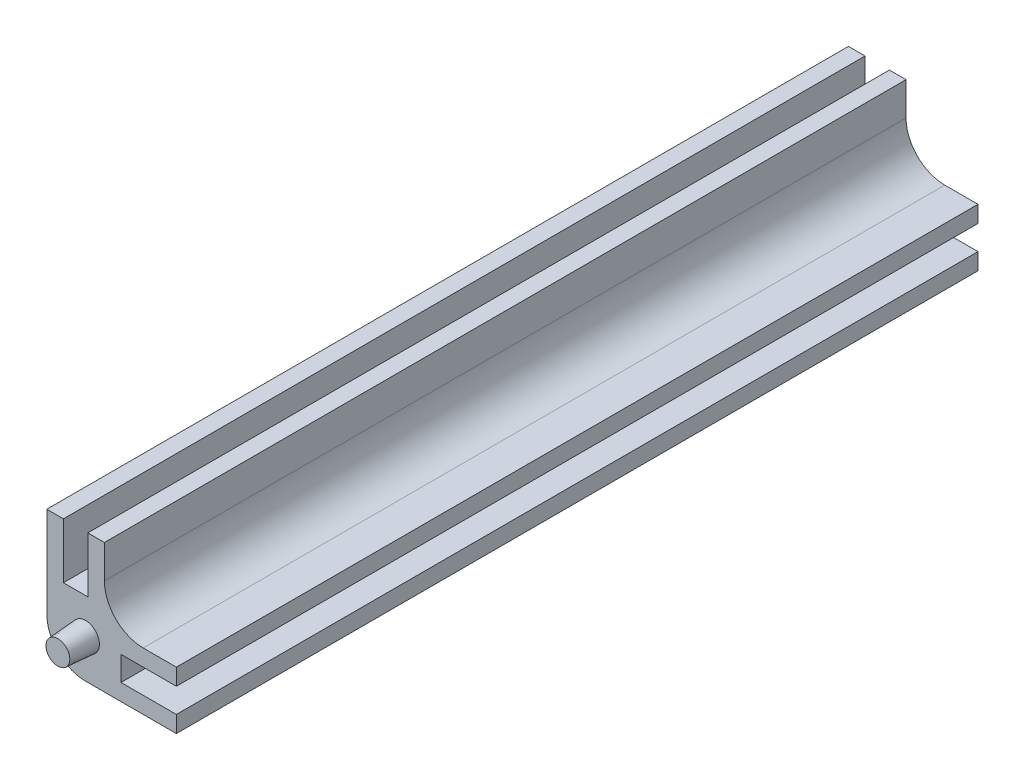
SolidWorks part; units mm, degrees
ref_plane "Спереди" through (0, 0, 0) normal (0, 0, 1) x (1, 0, 0)
ref_plane "Сверху" through (0, 0, 0) normal (0, 1, 0) x (1, 0, 0)
ref_plane "Справа" through (0, 0, 0) normal (1, 0, 0) x (0, 0, -1)
sketch "Sketch1" plane through (0, 0, 0) normal (0, 0, 1) x (1, 0, 0)
  line L0 (-3.4, -10.4) -> (13, -10.4)
  line L1 (13, -10.4) -> (13, -7.4)
  line L2 (13, -7.4) -> (3, -7.4)
  line L3 (3, -7.4) -> (3, -3)
  line L4 (3, -3) -> (13, -3)
  line L5 (13, -3) -> (13, 0)
  line L6 (13, 0) -> (7, 0)
  line L7 (0, 7) -> (0, 13)
  line L8 (0, 13) -> (-3, 13)
  line L9 (-3, 13) -> (-3, 3)
  line L10 (-3, 3) -> (-7.4, 3)
  line L11 (-7.4, 3) -> (-7.4, 13)
  line L12 (-7.4, 13) -> (-10.4, 13)
  line L13 (-10.4, 13) -> (-10.4, -3.4)
  arc A0 (0, 7) -> (7, 0) centre (7, 7) ccw
  arc A1 (-10.4, -3.4) -> (-3.4, -10.4) centre (-3.4, -3.4) ccw
  point P19 (0, 0)
  dimension "D5" = 7
  dimension "D1" = 4.4
  dimension "D2" = 3
  dimension "D3" = 10
  dimension "D4" = 3
extrude "Extrude1" add sketch "Sketch1" along normal blind 144.8
sketch "Sketch2" plane through (0, 0, 144.8) normal (0, 0, 1) x (1, 0, 0)
  circle A0 centre (-3.4, -3.4) radius 2.5
  dimension "D1" = 5
extrude "Extrude2" add sketch "Sketch2" along normal blind 5 draft 4
sketch "Sketch3" plane through (0, 0, 0) normal (0, 0, -1) x (-1, 0, 0)
  circle A0 centre (3.4, -3.4) radius 2.6
  dimension "D1" = 5.2
extrude "Cut-Extrude1" cut sketch "Sketch3" against normal blind 5.2 draft 3.8
sketch "Sketch5" [suppressed] plane through (0, 0, 0) normal (0, 0, -1) x (-1, 0, 0)
  line L1 (-3, -3) -> (-56.5699, -3)
  line L2 (-3, -3) -> (-3, 37.408)
  line L3 (-3, 37.408) -> (-56.5699, 37.408)
  line L4 (-56.5699, -3) -> (-56.5699, 37.408)
extrude "Extrude3" [suppressed] cut sketch "Sketch5" against normal through all
equation "\"pin_l\"=5"
equation "\"pin_skew\"=4"
equation "\"pin_r\"=5"
equation "\"thickness\"=4"
equation "\"M4_plastic_thread\"=3.8"
equation "\"M3_plastic_thread\" = 2.8"
equation "\"D1@Sketch2\"=\"pin_r\""
equation "\"D1@Extrude2\"=\"pin_l\""
equation "\"D3@Extrude2\"=\"pin_skew\""
equation "\"D1@Sketch3\"=\"pin_r\"+0.2"
equation "\"D1@Cut-Extrude1\"=\"pin_l\"+0.2"
equation "\"D3@Cut-Extrude1\"=\"pin_skew\"-0.2"
